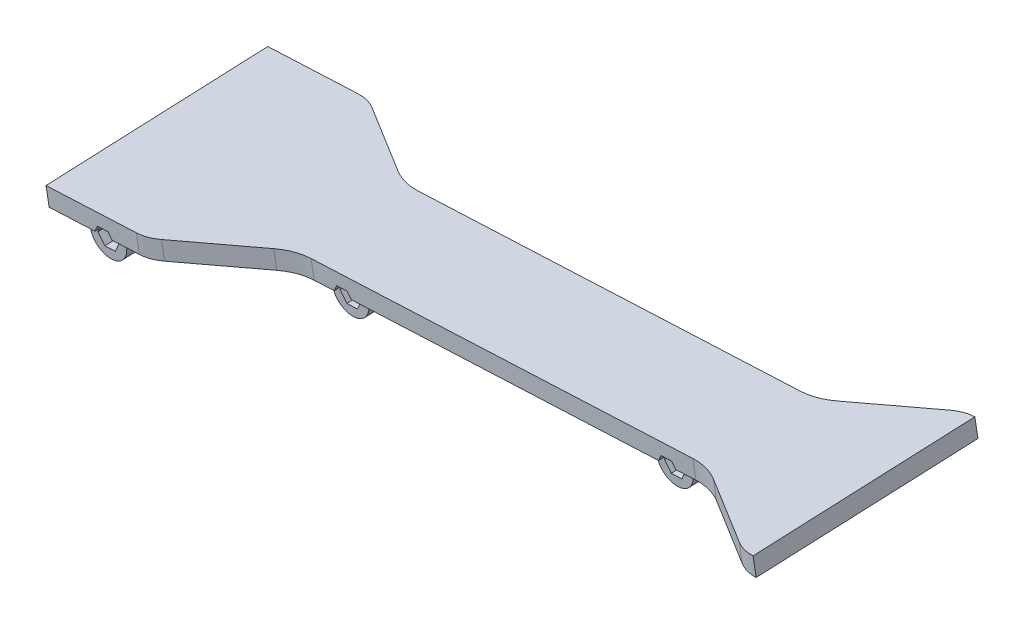
SolidWorks part; units mm, degrees
material "ABS"
ref_plane "前视基准面" through (0, 0, 0) normal (0, 0, 1) x (1, 0, 0)
ref_plane "上视基准面" through (0, 0, 0) normal (0, 1, 0) x (1, 0, 0)
ref_plane "右视基准面" through (0, 0, 0) normal (1, 0, 0) x (0, 0, -1)
other "Configuration Table"
sketch "草图1" plane through (-35.9528, 399.7424, 30.5662) normal (-0.0893, 0.9931, 0.0759) x (0.996, 0.0891, 0.0068)
  line L1 (300.0779, -1129.6043) -> (302.1051, -1072.2401)
  line L2 (300.0779, -1129.6043) -> (325.2788, -1130.4949)
  line L3 (300.0779, -1129.6043) -> (325.2788, -1130.4949)
  line L8 (491.8203, -1134.9123) -> (472.9431, -1123.1056)
  line L9 (464.9991, -1120.6732) -> (358.5617, -1116.9118)
  line L10 (350.4657, -1118.7774) -> (330.8022, -1129.2221)
  line L11 (325.2788, -1130.4949) -> (302.5764, -1129.6926)
  line L12 (491.8203, -1134.9123) -> (472.9431, -1123.1056)
  line L13 (464.9991, -1120.6732) -> (358.5617, -1116.9118)
  line L14 (350.4657, -1118.7774) -> (330.8022, -1129.2221)
  line L17 (499.2673, -1079.2076) -> (497.2401, -1136.5718)
  line L20 (474.0803, -1090.9251) -> (493.7439, -1080.4804)
  line L21 (359.547, -1089.0293) -> (465.9844, -1092.7906)
  line L22 (332.7258, -1074.7901) -> (351.603, -1086.5969)
  line L23 (302.1051, -1072.2401) -> (327.306, -1073.1307)
  line L24 (474.0803, -1090.9251) -> (493.7439, -1080.4804)
  line L25 (359.547, -1089.0293) -> (465.9844, -1092.7906)
  line L26 (332.7258, -1074.7901) -> (351.603, -1086.5969)
  line L27 (302.1051, -1072.2401) -> (327.306, -1073.1307)
  arc A8 (491.8203, -1134.9123) -> (497.2401, -1136.5718) centre (497.6268, -1125.6286) ccw
  arc A9 (472.9431, -1123.1056) -> (464.9991, -1120.6732) centre (464.4322, -1136.7132) ccw
  arc A10 (358.5617, -1116.9118) -> (350.4657, -1118.7774) centre (357.9948, -1132.9518) ccw
  arc A11 (325.2788, -1130.4949) -> (330.8022, -1129.2221) centre (325.6655, -1119.5517) ccw
  arc A12 (491.8203, -1134.9123) -> (497.2401, -1136.5718) centre (497.6268, -1125.6286) ccw
  arc A13 (472.9431, -1123.1056) -> (464.9991, -1120.6732) centre (464.4322, -1136.7132) ccw
  arc A14 (358.5617, -1116.9118) -> (350.4657, -1118.7774) centre (357.9948, -1132.9518) ccw
  arc A15 (325.2788, -1130.4949) -> (330.8022, -1129.2221) centre (325.6655, -1119.5517) ccw
  arc A20 (499.2673, -1079.2076) -> (493.7439, -1080.4804) centre (498.8805, -1090.1508) ccw
  arc A21 (465.9844, -1092.7906) -> (474.0803, -1090.9251) centre (466.5512, -1076.7507) ccw
  arc A22 (351.603, -1086.5969) -> (359.547, -1089.0293) centre (360.1139, -1072.9893) ccw
  arc A23 (332.7258, -1074.7901) -> (327.306, -1073.1307) centre (326.9193, -1084.0738) ccw
  arc A24 (499.2673, -1079.2076) -> (493.7439, -1080.4804) centre (498.8805, -1090.1508) ccw
  arc A25 (465.9844, -1092.7906) -> (474.0803, -1090.9251) centre (466.5512, -1076.7507) ccw
  arc A26 (351.603, -1086.5969) -> (359.547, -1089.0293) centre (360.1139, -1072.9893) ccw
  arc A27 (332.7258, -1074.7901) -> (327.306, -1073.1307) centre (326.9193, -1084.0738) ccw
  dimension "D3" = 1.05
  dimension "D1" = 1.05
  dimension "D2" = 1.05
extrude "凸台-拉伸1" add sketch "草图1" against normal blind 5
ref_plane "基准面1" through (-38.3276, -86.449, 1085.4905) normal (-0.0352, -0.0793, 0.9962) x (0.9994, -0.0028, 0.0351)
sketch "草图2" plane through (-38.3276, -86.449, 1085.4905) normal (-0.0352, -0.0793, 0.9962) x (0.9994, -0.0028, 0.0351)
  circle A2 centre (318.142, 426.6596) radius 1.6 construction
  circle A3 centre (318.142, 426.6596) radius 5
  circle A4 centre (318.142, 426.6596) radius 1.6 construction
  dimension "D1" = 10
extrude "凸台-拉伸3" add sketch "草图2" along normal mid plane 55
sketch "草图3" plane through (-39.3371, -88.726, 1114.0822) normal (-0.0352, -0.0793, 0.9962) x (0.9994, -0.0028, 0.0351)
  line L1 (321.1034, 426.9254) -> (319.3926, 429.3572)
  line L2 (319.3926, 429.3572) -> (316.4311, 429.0915)
  line L3 (316.4311, 429.0915) -> (315.1805, 426.3939)
  line L4 (315.1805, 426.3939) -> (316.8914, 423.9621)
  line L5 (316.8914, 423.9621) -> (319.8529, 424.2278)
  line L6 (319.8529, 424.2278) -> (321.1034, 426.9254)
  line L7 (302.45, 431.2756) -> (327.5657, 433.5294) construction
  circle A0 centre (318.142, 426.6596) radius 2.575 construction
  dimension "D1" = 5.15
extrude "切除-拉伸1" cut sketch "草图3" against normal blind 59.8
sketch "草图4" plane through (-38.3276, -86.449, 1085.4905) normal (-0.0352, -0.0793, 0.9962) x (0.9994, -0.0028, 0.0351)
  circle A0 centre (368.7211, 431.1983) radius 5
  circle A1 centre (458.8628, 439.2871) radius 5
  dimension "D1" = 10
  dimension "D2" = 10
extrude "凸台-拉伸4" add sketch "草图4" along normal mid plane 24
sketch "草图5" plane through (-38.8183, -87.5557, 1099.3878) normal (-0.0352, -0.0793, 0.9962) x (0.9994, -0.0028, 0.0351)
  line L0 (360.2169, 436.4593) -> (466.2945, 445.9781) construction
  line L1 (369.9717, 433.8959) -> (367.0103, 433.6301)
  line L2 (367.0103, 433.6301) -> (365.7597, 430.9326)
  line L3 (365.7597, 430.9326) -> (367.4705, 428.5008)
  line L4 (367.4705, 428.5008) -> (370.432, 428.7665)
  line L5 (370.432, 428.7665) -> (371.6826, 431.4641)
  line L6 (371.6826, 431.4641) -> (369.9717, 433.8959)
  line L7 (460.1134, 441.9847) -> (457.1519, 441.7189)
  line L8 (457.1519, 441.7189) -> (455.9013, 439.0214)
  line L9 (455.9013, 439.0214) -> (457.6122, 436.5895)
  line L10 (457.6122, 436.5895) -> (460.5736, 436.8553)
  line L11 (460.5736, 436.8553) -> (461.8242, 439.5528)
  line L12 (461.8242, 439.5528) -> (460.1134, 441.9847)
  circle A0 centre (368.7211, 431.1983) radius 2.575 construction
  circle A1 centre (458.8628, 439.2871) radius 2.575 construction
  dimension "D1" = 5.15
  dimension "D2" = 5.15
extrude "切除-拉伸2" cut sketch "草图5" against normal blind 39
fillet "圆角1" radius 2 6 edges at (425.0382, 351.5862, 1136.7368) (415.2855, 350.7405, 1136.3251) (334.9524, 343.7746, 1132.9338) (325.1997, 342.929, 1132.5221) (284.4045, 339.3915, 1130.8) (274.6518, 338.5459, 1130.3883)
sketch "草图6" plane through (-39.2949, -88.6308, 1112.8867) normal (-0.0352, -0.0793, 0.9962) x (0.9994, -0.0028, 0.0351)
  circle A0 centre (318.142, 426.6596) radius 5
  circle A1 centre (318.142, 426.6596) radius 1.9
  dimension "D1" = 10
  dimension "D2" = 3.8
extrude "凸台-拉伸5" [suppressed] add sketch "草图6" against normal blind 2.5
sketch "草图7" plane through (-38.7497, -87.401, 1097.4452) normal (-0.0352, -0.0793, 0.9962) x (0.9994, -0.0028, 0.0351)
  circle A0 centre (368.7211, 431.1983) radius 5
  circle A1 centre (368.7211, 431.1983) radius 1.9
  circle A2 centre (458.8628, 439.2871) radius 5
  circle A3 centre (458.8628, 439.2871) radius 1.9
  dimension "D1" = 10
  dimension "D2" = 3.8
  dimension "D3" = 10
  dimension "D4" = 3.8
extrude "凸台-拉伸6" [suppressed] add sketch "草图7" against normal blind 2
mirror "镜向1" [suppressed] about plane through (-38.3276, -86.449, 1085.4905) normal (-0.0352, -0.0793, 0.9962)
sketch "草图8" plane through (534.5897, 46.3554, 22.5676) normal (0.9954, 0.0863, 0.042) x (0.0419, 0.0036, -0.9991)
  line L0 (-1088.4263, 320.7205) -> (-1088.526, 320.7129)
  line L1 (-1145.6603, 316.3578) -> (-1088.4263, 320.7205) construction
  line L2 (-1088.526, 320.7129) -> (-1088.146, 315.7274)
  line L3 (-1145.2803, 311.3723) -> (-1088.0463, 315.735) construction
  line L4 (-1088.146, 315.7274) -> (-1088.0463, 315.735)
  line L5 (-1088.0463, 315.735) -> (-1088.4263, 320.7205)
  dimension "D1" = 0.1
sketch3d "3D草图1"
  line L0 (290.0449, 347.0744, 1102.8023) -> (264.9448, 344.8979, 1101.7427) construction
  line L1 (314.2448, 348.2116, 1116.3948) -> (295.4431, 347.4305, 1104.4938) construction
  line L2 (428.169, 357.9261, 1123.3494) -> (322.1571, 348.7336, 1118.8741) construction
  line L3 (455.8175, 361.3369, 1111.264) -> (436.2326, 358.7894, 1121.5444) construction
  line L4 (290.0449, 347.0744, 1102.8023) -> (264.9448, 344.8979, 1101.7427)
  line L5 (314.2448, 348.2116, 1116.3948) -> (295.4431, 347.4305, 1104.4938)
  line L6 (428.169, 357.9261, 1123.3494) -> (322.1571, 348.7336, 1118.8741)
  line L7 (455.8175, 361.3369, 1111.264) -> (436.2326, 358.7894, 1121.5444)
  arc A0 (295.4431, 347.4305, 1104.4938) -> (290.0449, 347.0744, 1102.8023) centre (289.6598, 346.2056, 1113.711) ccw construction
  arc A1 (322.1571, 348.7336, 1118.8741) -> (314.2448, 348.2116, 1116.3948) centre (322.7216, 350.007, 1102.8847) ccw construction
  arc A2 (436.2326, 358.7894, 1121.5444) -> (428.169, 357.9261, 1123.3494) centre (428.7336, 359.1995, 1107.36) ccw construction
  arc A3 (461.3189, 361.9259, 1110.0326) -> (455.8175, 361.3369, 1111.264) centre (460.9337, 361.0571, 1120.9413) ccw construction
  arc A4 (295.4431, 347.4305, 1104.4938) -> (290.0449, 347.0744, 1102.8023) centre (289.6598, 346.2056, 1113.711) ccw
  arc A5 (322.1571, 348.7336, 1118.8741) -> (314.2448, 348.2116, 1116.3948) centre (322.7216, 350.007, 1102.8847) ccw
  arc A6 (436.2326, 358.7894, 1121.5444) -> (428.169, 357.9261, 1123.3494) centre (428.7336, 359.1995, 1107.36) ccw
  arc A7 (461.3189, 361.9259, 1110.0326) -> (455.8175, 361.3369, 1111.264) centre (460.9337, 361.0571, 1120.9413) ccw
  point P5 (288.6817, 357.0801, 1114.5425)
  point P9 (324.1552, 334.0677, 1101.6659)
  point P13 (430.1672, 343.2602, 1106.1412)
  point P16 (288.6817, 357.0801, 1114.5425)
  point P17 (459.9556, 371.9316, 1121.7728)
  point P18 (324.1552, 334.0677, 1101.6659)
  point P19 (430.1672, 343.2602, 1106.1412)
  point P20 (459.9556, 371.9316, 1121.7728)
sweep "切除-扫描1" cut profiles "草图8" path "3D草图1"
mirror "镜向2" about plane through (-38.3276, -86.449, 1085.4905) normal (-0.0352, -0.0793, 0.9962) of "切除-扫描1"
sketch "草图10" [suppressed] plane through (-38.6794, -87.2424, 1095.4528) normal (0.0352, 0.0793, -0.9962) x (-0.9994, 0.0028, -0.0351)
  circle A0 centre (-458.8628, 439.2871) radius 1.9
  circle A1 centre (-458.8628, 439.2871) radius 1.9 construction
  circle A2 centre (-368.7211, 431.1983) radius 1.9
  circle A3 centre (-368.7211, 431.1983) radius 1.9 construction
extrude "凸台-拉伸7" [suppressed] add sketch "草图10" against normal offset from surface (12 mm away) 10
sketch "草图11" [suppressed] plane through (-39.207, -88.4325, 1110.3962) normal (0.0352, 0.0793, -0.9962) x (-0.9994, 0.0028, -0.0351)
  circle A0 centre (-318.142, 426.6596) radius 1.9
  circle A1 centre (-318.142, 426.6596) radius 1.9 construction
extrude "凸台-拉伸8" [suppressed] add sketch "草图11" against normal offset from surface (12.5 mm away) 10
mirror "镜向3" about plane through (-38.3276, -86.449, 1085.4905) normal (-0.0352, -0.0793, 0.9962) of bodies 117 119
